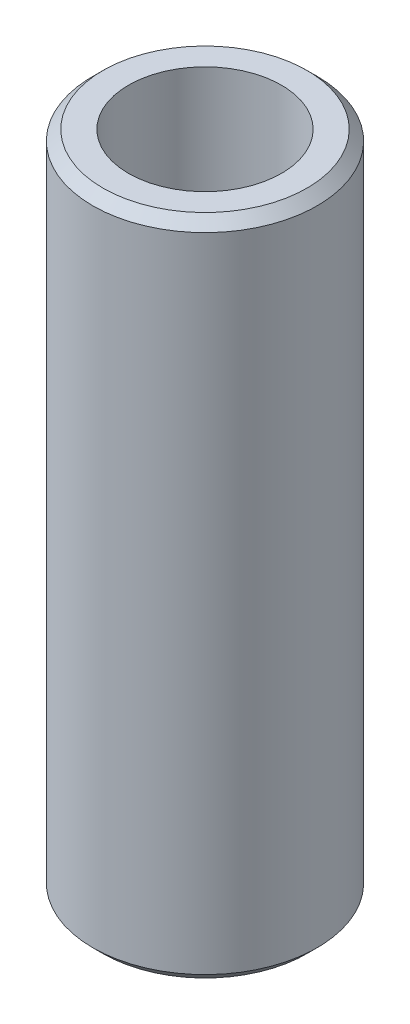
SolidWorks part; units mm, degrees
material "1.7131 (16MnCr5)"
ref_plane "Front Plane" through (0, 0, 0) normal (0, 0, 1) x (1, 0, 0)
ref_plane "Top Plane" through (0, 0, 0) normal (0, 1, 0) x (1, 0, 0)
ref_plane "Right Plane" through (0, 0, 0) normal (1, 0, 0) x (0, 0, -1)
sketch "Sketch1" plane through (0, 0, 0) normal (0, 1, 0) x (1, 0, 0)
  circle A0 centre (0, 0) radius 22
  circle A1 centre (0, 0) radius 15
  dimension "D1" = 30
  dimension "D2" = 44
extrude "Boss-Extrude1" add sketch "Sketch1" against normal blind 130
chamfer "Chamfer1" distance 2 angle 45 2 edges at (0, 0, 22) (0, -130, 22)
